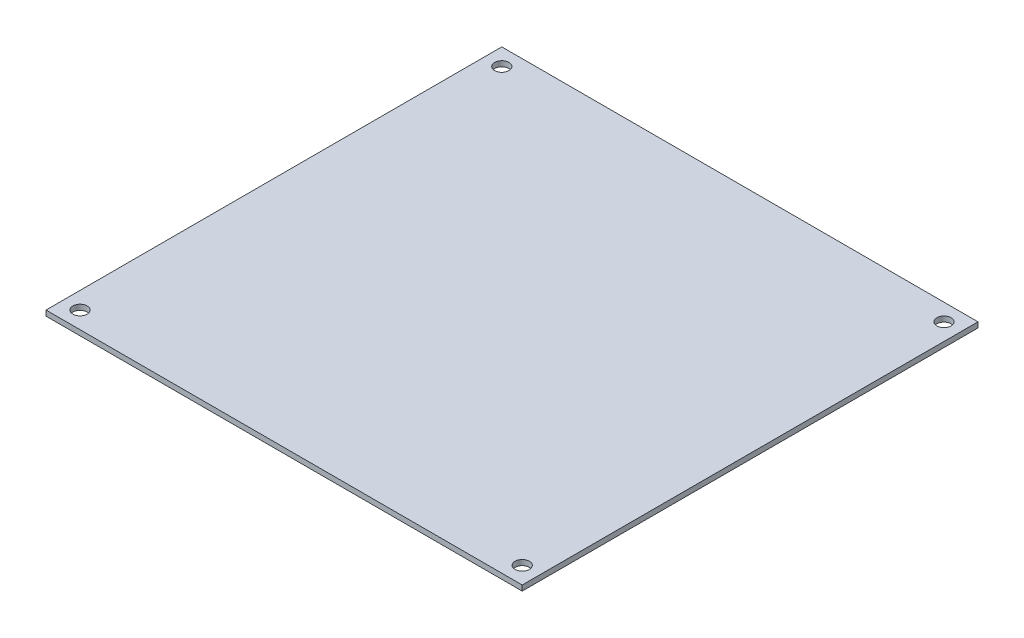
SolidWorks part; units mm, degrees
ref_plane "Front" through (0, 0, 0) normal (0, 0, 1) x (1, 0, 0)
ref_plane "Top" through (0, 0, 0) normal (0, 1, 0) x (1, 0, 0)
ref_plane "Right" through (0, 0, 0) normal (1, 0, 0) x (0, 0, -1)
sketch "Sketch1" plane through (0, 0, 0) normal (0, 1, 0) x (1, 0, 0)
  line L0 (0, 134) -> (140, 0) construction
  line L1 (0, 0) -> (140, 0)
  line L2 (0, 0) -> (0, 134)
  line L3 (0, 134) -> (140, 134)
  line L4 (140, 0) -> (140, 134)
  line L5 (140, 134) -> (0, 0) construction
  line L7 (5, 5) -> (135, 5) construction
  line L8 (5, 5) -> (5, 129) construction
  line L9 (5, 129) -> (135, 129) construction
  line L10 (135, 5) -> (135, 129) construction
  line L11 (5, 5) -> (135, 129) construction
  line L12 (5, 129) -> (135, 5) construction
  circle A1 centre (5, 129) radius 2.1
  circle A2 centre (135, 129) radius 2.1
  circle A3 centre (135, 5) radius 2.1
  circle A4 centre (5, 5) radius 2.1
  point P4 (70, 67)
  dimension "D3" = 124
  dimension "D6" = 4.2
  dimension "D1" = 140
  dimension "D2" = 134
  dimension "D4" = 130
extrude "Boss-Extrude1" add sketch "Sketch1" along normal blind 1.57
